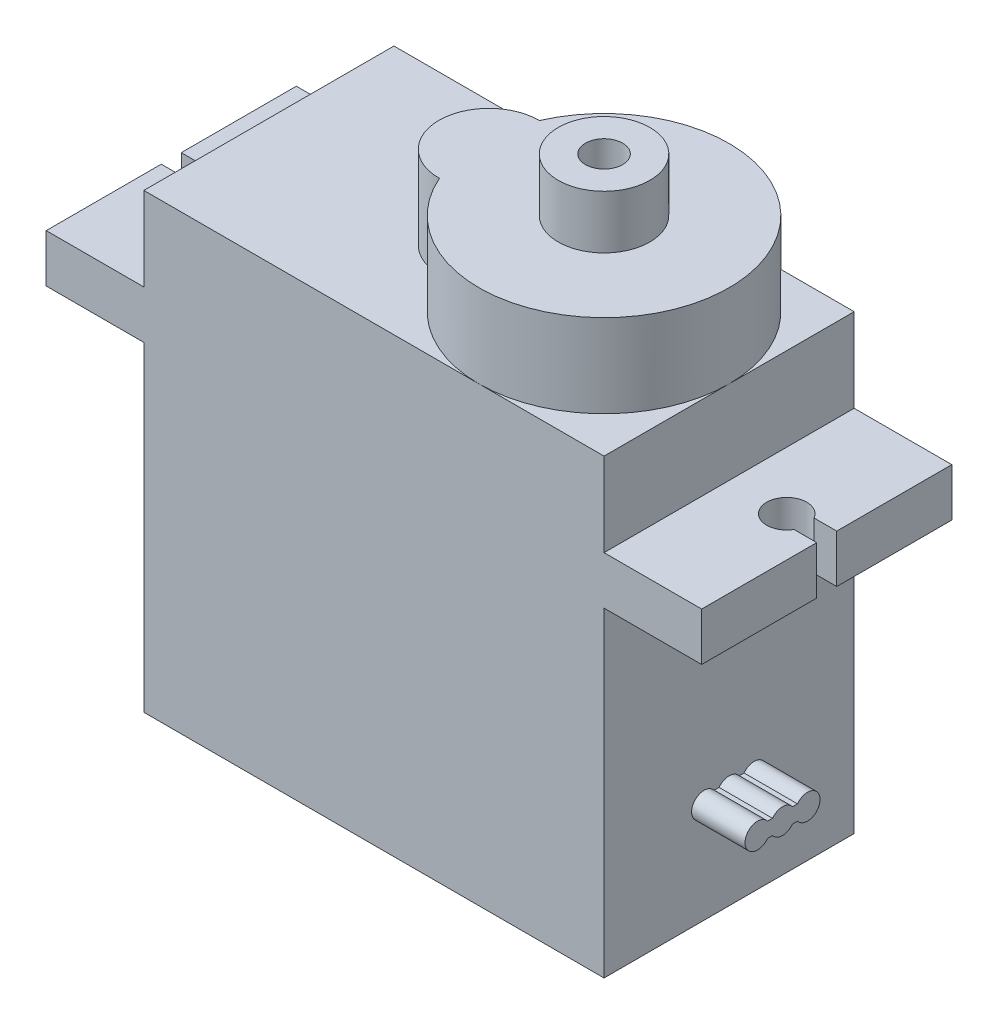
SolidWorks part; units mm, degrees
ref_plane "Front Plane" through (0, 0, 0) normal (0, 0, 1) x (1, 0, 0)
ref_plane "Top Plane" through (0, 0, 0) normal (0, 1, 0) x (1, 0, 0)
ref_plane "Right Plane" through (0, 0, 0) normal (1, 0, 0) x (0, 0, -1)
sketch "Sketch1" plane through (0, 0, 0) normal (0, 1, 0) x (1, 0, 0)
  line L1 (0, 0) -> (23, 0)
  line L2 (0, 0) -> (0, 12.5)
  line L3 (0, 12.5) -> (23, 12.5)
  line L4 (23, 0) -> (23, 12.5)
  dimension "D1" = 23
  dimension "D2" = 12.5
extrude "Boss-Extrude1" add sketch "Sketch1" along normal blind 22.59
sketch "Sketch2" plane through (0, 22.59, 0) normal (0, 1, 0) x (1, 0, 0)
  line L0 (23, 0) -> (23, 12.5) construction
  line L1 (0, 0) -> (23, 0) construction
  line L2 (23, 12.5) -> (0, 12.5) construction
  circle A0 centre (16.75, 6.25) radius 6.25
extrude "Boss-Extrude2" add sketch "Sketch2" along normal blind 4.16
sketch "Sketch3" plane through (0, 22.59, 0) normal (0, 1, 0) x (1, 0, 0)
  line L0 (23, 0) -> (23, 6.25) construction
  line L1 (0, 12.5) -> (0, 0) construction
  circle A0 centre (11, 6.25) radius 2.5
  point P4 (0, 6.25)
  dimension "D1" = 5
  dimension "D2" = 12
extrude "Boss-Extrude3" add sketch "Sketch3" along normal up to surface (4.16 mm away) up to face at (16.75, 26.75, 0)
sketch "Sketch6" plane through (0, 26.75, 0) normal (0, 1, 0) x (1, 0, 0)
  circle A0 centre (16.75, 6.25) radius 2.29
  arc A1 (11.0217, 3.7501) -> (11.0217, 8.7499) centre (16.75, 6.25) ccw construction
  arc A2 (11.0217, 3.7501) -> (11.0217, 8.7499) centre (16.75, 6.25) ccw construction
  circle A3 centre (16.75, 6.25) radius 0.93
  dimension "D1" = 4.58
  dimension "D2" = 1.86
extrude "Boss-Extrude5" add sketch "Sketch6" along normal blind 2.67 separate body
sketch "Sketch4" plane through (23, 0, 0) normal (1, 0, 0) x (0, 0, -1)
  line L0 (0, 22.59) -> (0, 0) construction
  line L1 (0, 18.41) -> (12.5, 18.41)
  line L2 (0, 18.41) -> (0, 16.01)
  line L3 (0, 16.01) -> (12.5, 16.01)
  line L4 (12.5, 18.41) -> (12.5, 16.01)
  line L5 (12.5, 22.59) -> (12.5, 0) construction
  line L6 (6.25, 22.59) -> (12.5, 22.59) construction
  dimension "D1" = 4.18
  dimension "D2" = 2.4
extrude "Boss-Extrude4" add sketch "Sketch4" along normal blind 4.88
sketch "Sketch5" plane through (0, 18.41, 0) normal (0, 1, 0) x (1, 0, 0)
  line L0 (27.88, 12.5) -> (27.88, 0) construction
  line L1 (27.88, 12.5) -> (23, 12.5) construction
  line L3 (25.88, 6.75) -> (27.88, 6.75)
  line L4 (25.88, 6.75) -> (25.88, 5.75)
  line L5 (25.88, 5.75) -> (27.88, 5.75)
  line L6 (27.88, 6.75) -> (27.88, 5.75)
  circle A0 centre (25.88, 6.25) radius 1
  point P2 (27.88, 6.25)
  point P3 (25.44, 12.5)
  point P12 (27.88, 6.25)
  line M3 (27.88, 0) -> (27.88, 12.5)
  dimension "D1" = 2
  dimension "D2" = 2
  dimension "D3" = 1
extrude "Cut-Extrude1" cut sketch "Sketch5" against normal through all contours L3 A0 L5 L4 | L5 A0 L3 L4 | A0 L5 L3 M3
ref_plane "Plane1" through (11.5, 0, 0) normal (1, 0, 0) x (0, 0, -1)
mirror "Mirror1" about plane through (11.5, 0, 0) normal (1, 0, 0) of "Boss-Extrude4", "Cut-Extrude1"
sketch "Sketch7" plane through (23, 0, 0) normal (1, 0, 0) x (0, 0, -1)
  line L0 (0, 0) -> (12.5, 0) construction
  line L2 (6.9988, 5.3734) -> (5.5012, 5.3734)
  line L3 (6.9988, 5.3734) -> (6.9988, 4.6266)
  line L4 (6.9988, 4.6266) -> (5.5012, 4.6266)
  line L5 (5.5012, 5.3734) -> (5.5012, 4.6266)
  circle A0 centre (7.5, 5) radius 0.625
  circle A1 centre (6.25, 5) radius 0.625
  circle A2 centre (5, 5) radius 0.625
  point P6 (6.25, 0)
  dimension "D1" = 1.25
  dimension "D2" = 5
  dimension "D3" = 0.7469
extrude "Boss-Extrude7" add sketch "Sketch7" along normal blind 2.67 contours L3 A0 | L2 A1 | L4 A1 | L3 A0 | A2 L5 | L5 A2
